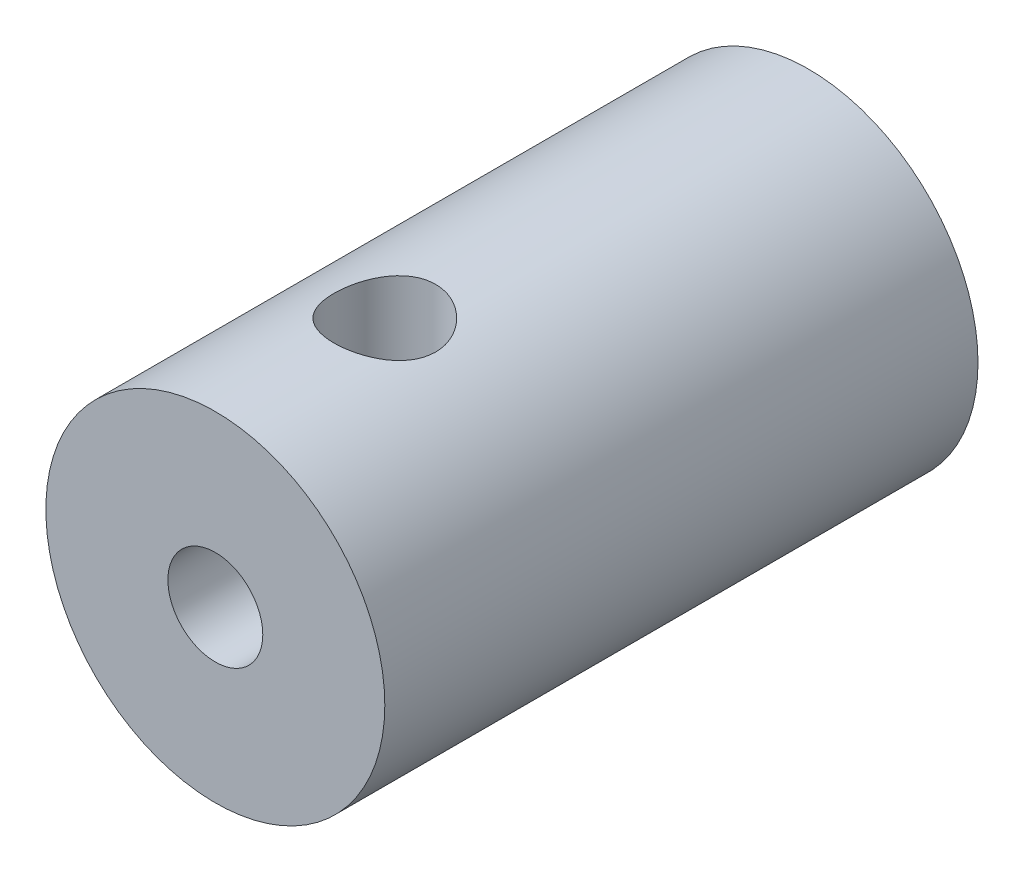
SolidWorks part; units mm, degrees
ref_plane "Front Plane" through (0, 0, 0) normal (0, 0, 1) x (1, 0, 0)
ref_plane "Top Plane" through (0, 0, 0) normal (0, 1, 0) x (1, 0, 0)
ref_plane "Right Plane" through (0, 0, 0) normal (1, 0, 0) x (0, 0, -1)
sketch "Sketch1" plane through (0, 0, 0) normal (0, 0, 1) x (1, 0, 0)
  circle A0 centre (0, 0) radius 10
  dimension "D1" = 20
extrude "Boss-Extrude1" add sketch "Sketch1" along normal blind 35 contours A0
ref_plane "Plane1" through (0, 0, 12) normal (0, 0, -1) x (-1, 0, 0)
sketch "Sketch2" plane through (0, 0, 12) normal (0, 0, -1) x (-1, 0, 0)
  circle A0 centre (0, 0) radius 2.9
  dimension "D1" = 5.8
extrude "Cut-Extrude1" cut sketch "Sketch2" along normal up to surface (12 mm away) draft 1
sketch "Sketch3" plane through (0, 0, 0) normal (0, 1, 0) x (1, 0, 0)
  line L0 (0, 0) -> (0, -35) construction
  line L1 (10, 0) -> (-10, 0) construction
  line L2 (-10, -35) -> (10, -35) construction
  circle A0 centre (0, -25) radius 3
  dimension "D1" = 6
  dimension "D2" = 10
extrude "Cut-Extrude2" cut sketch "Sketch3" against normal through all and the other way through all
sketch "Sketch4" plane through (0, 0, 35) normal (0, 0, 1) x (1, 0, 0)
  circle A0 centre (0, 0) radius 2.8
  dimension "D1" = 5.6
extrude "Cut-Extrude3" cut sketch "Sketch4" against normal up to surface (8.923 mm away)
